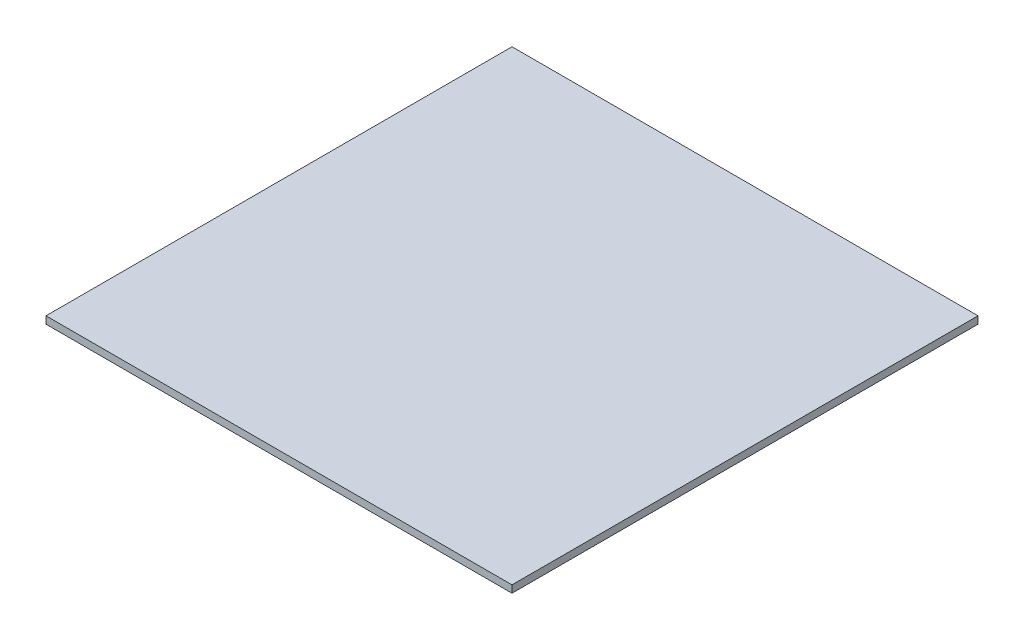
SolidWorks part; units mm, degrees
material "Pine"
ref_plane "Front" through (0, 0, 0) normal (0, 0, 1) x (1, 0, 0)
ref_plane "Top" through (0, 0, 0) normal (0, 1, 0) x (1, 0, 0)
ref_plane "Right" through (0, 0, 0) normal (1, 0, 0) x (0, 0, -1)
sketch "Sketch1" plane through (0, 0, 0) normal (0, 1, 0) x (1, 0, 0)
  line L1 (-609.6, 1219.2) -> (609.6, 1219.2)
  line L2 (-609.6, 1219.2) -> (-609.6, 0)
  line L3 (-609.6, 0) -> (609.6, 0)
  line L4 (609.6, 1219.2) -> (609.6, 0)
  dimension "D1" = 1219.2
  dimension "D2" = 1219.2
extrude "Extrude1" add sketch "Sketch1" against normal blind 19.05
